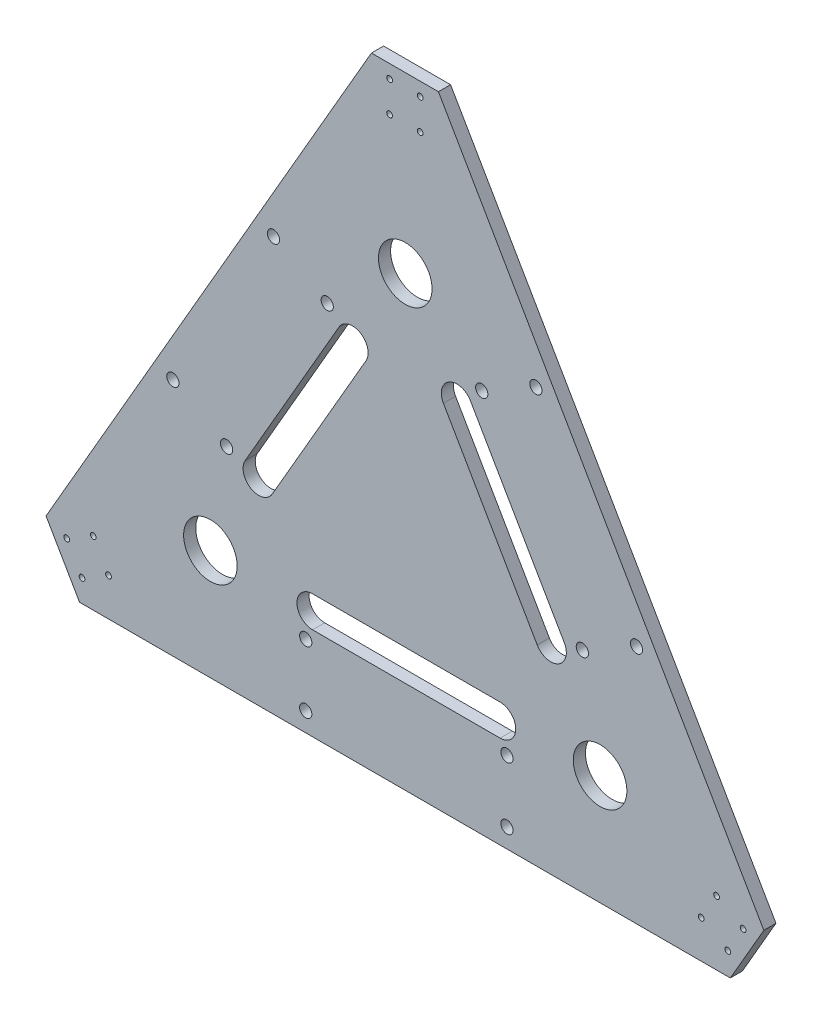
SolidWorks part; units mm, degrees
ref_plane "Front Plane" through (0, 0, 0) normal (0, 0, 1) x (1, 0, 0)
ref_plane "Top Plane" through (0, 0, 0) normal (0, 1, 0) x (1, 0, 0)
ref_plane "Right Plane" through (0, 0, 0) normal (1, 0, 0) x (0, 0, -1)
sketch "Sketch1" plane through (0, 0, 0) normal (0, 0, 1) x (1, 0, 0)
  line L0 (-647.4603, -317.6195) -> (-477.476, -23.1982)
  line L1 (-477.476, -23.1982) -> (-442.476, -23.1982)
  line L2 (-442.476, -23.1982) -> (-272.4917, -317.6195)
  line L3 (-272.4917, -317.6195) -> (-289.9917, -347.9304)
  line L4 (-289.9917, -347.9304) -> (-629.9603, -347.9304)
  line L5 (-629.9603, -347.9304) -> (-647.4603, -317.6195)
  line L6 (-432.8097, -158.7631) -> (-383.8097, -243.6336) construction
  line L7 (-425.7508, -154.6876) -> (-376.7508, -239.5581)
  line L8 (-439.8686, -162.8385) -> (-390.8686, -247.709)
  line L9 (-410.2405, -291.3785) -> (-508.2405, -291.3785) construction
  line L10 (-410.2405, -299.5293) -> (-508.2405, -299.5293)
  line L11 (-410.2405, -283.2276) -> (-508.2405, -283.2276)
  line L12 (-536.3734, -244.6163) -> (-487.3734, -159.7458) construction
  line L13 (-543.4323, -240.5408) -> (-494.4323, -155.6703)
  line L14 (-529.3145, -248.6917) -> (-480.3145, -163.8212)
  line L15 (-459.8079, -231.5859) -> (-432.8097, -158.7631) construction
  line L16 (-459.8079, -231.5859) -> (-459.8079, -114.0541) construction
  circle A1 centre (-581.2092, -222.8693) radius 3.2
  circle A2 centre (-528.6492, -131.8327) radius 3.2
  circle A3 centre (-500.5777, -148.0115) radius 3.2
  circle A4 centre (-553.1368, -239.0465) radius 3.2
  circle A13 centre (-367.2942, -238.2091) radius 3.2
  circle A14 centre (-419.8542, -147.1725) radius 3.2
  circle A15 centre (-391.5457, -131.4121) radius 3.2
  circle A16 centre (-338.9857, -222.4487) radius 3.2
  circle A17 centre (-511.8008, -305.5304) radius 3.2
  circle A18 centre (-406.6805, -305.5304) radius 3.2
  circle A19 centre (-406.6806, -337.9304) radius 3.2
  circle A20 centre (-511.8006, -337.9304) radius 3.2
  arc A21 (-425.7508, -154.6876) -> (-439.8686, -162.8385) centre (-432.8097, -158.7631) ccw
  arc A22 (-390.8686, -247.709) -> (-376.7508, -239.5581) centre (-383.8097, -243.6336) ccw
  arc A23 (-410.2405, -299.5293) -> (-410.2405, -283.2276) centre (-410.2405, -291.3785) ccw
  arc A24 (-508.2405, -283.2276) -> (-508.2405, -299.5293) centre (-508.2405, -291.3785) ccw
  arc A25 (-543.4323, -240.5408) -> (-529.3145, -248.6917) centre (-536.3734, -244.6163) ccw
  arc A26 (-480.3145, -163.8212) -> (-494.4323, -155.6703) centre (-487.3734, -159.7458) ccw
  circle A27 centre (-459.8079, -114.0541) radius 14
  circle A28 centre (-358.0223, -290.3519) radius 14
  circle A29 centre (-561.5935, -290.3519) radius 14
  point P6 (-526.8577, -193.5298)
  point P17 (-393.5776, -192.6927)
  point P18 (-408.3097, -201.1983)
  point P20 (-459.8079, -231.5859)
  point P29 (-459.2405, -305.5304)
  point P46 (-459.2405, -291.3785)
  point P53 (-511.8734, -202.181)
  dimension "D5" = 32.4
  dimension "D6" = 52.56
  dimension "D16" = 10
  dimension "D28" = 6.4
  dimension "D30" = 6.4
  dimension "D4" = 105.1182
  dimension "D7" = 105.12
  dimension "D8" = 32.4
  dimension "D9" = 10
  dimension "D10" = 42.4
  dimension "D11" = 52.56
  dimension "D12" = 110
  dimension "D13" = 10
  dimension "D14" = 105.12
  dimension "D15" = 110
  dimension "D17" = 32.4
  dimension "D18" = 77.6664
  dimension "D19" = 105.12
  dimension "D20" = 10
  dimension "D21" = 42.4
  dimension "D22" = 10
  dimension "D23" = 10
  dimension "D24" = 339.9685
  dimension "D25" = 32.4
  dimension "D27" = 52.56
  dimension "D29" = 105.12
  dimension "D31" = 42.4
  dimension "D33" = 3
  dimension "D36" = 3
sketch "Sketch2" plane through (0, 0, 0) normal (0, 0, 1) x (1, 0, 0)
  line L0 (-289.9917, -347.9304) -> (-629.9603, -347.9304) construction
  line L1 (-631.9603, -344.4663) -> (-645.4603, -321.0836)
  line L2 (-631.9603, -344.4663) -> (-605.9795, -329.4663)
  line L3 (-605.9795, -329.4663) -> (-619.4795, -306.0836)
  line L4 (-645.4603, -321.0836) -> (-619.4795, -306.0836)
  line L5 (-473.476, -23.1982) -> (-446.476, -23.1982)
  line L10 (-473.476, -23.1982) -> (-473.476, -53.1982)
  line L11 (-473.476, -53.1982) -> (-446.476, -53.1982)
  line L12 (-446.476, -23.1982) -> (-446.476, -53.1982)
  line L14 (-477.476, -23.1982) -> (-442.476, -23.1982) construction
  line L15 (-629.9603, -347.9304) -> (-647.4603, -317.6195) construction
  line L16 (-274.4867, -321.0749) -> (-287.9968, -344.4751)
  line L17 (-274.4867, -321.0749) -> (-300.4775, -306.0924)
  line L18 (-300.4775, -306.0924) -> (-313.9775, -329.475)
  line L19 (-287.9968, -344.4751) -> (-313.9775, -329.475)
  circle A0 centre (-636.6481, -322.3468) radius 1.5
  circle A1 centre (-628.6481, -336.2032) radius 1.5
  circle A2 centre (-614.7917, -328.2032) radius 1.5
  circle A3 centre (-622.7917, -314.3468) radius 1.5
  circle A8 centre (-451.976, -30.1982) radius 1.5
  circle A9 centre (-467.976, -30.1982) radius 1.5
  circle A10 centre (-467.976, -46.1982) radius 1.5
  circle A11 centre (-451.976, -46.1982) radius 1.5
  circle A12 centre (-291.3089, -336.2119) radius 1.5
  circle A13 centre (-283.309, -322.3555) radius 1.5
  circle A14 centre (-297.163, -314.3514) radius 1.5
  circle A15 centre (-305.1654, -328.2119) radius 1.5
  point P10 (-465.8216, -193.3804)
  point P41 (-459.976, -23.1982)
  point P44 (-459.976, -23.1982)
  point P50 (-638.7103, -332.775)
  point P51 (-638.7103, -332.775)
  dimension "D3" = 3
  dimension "D12" = 3
  dimension "D22" = 3
  dimension "D1" = 27
  dimension "D2" = 30
  dimension "D4" = 7
  dimension "D7" = 16
  dimension "D8" = 5.5
  dimension "D9" = 154.55
  dimension "D10" = 27
  dimension "D11" = 30
  dimension "D13" = 7
  dimension "D14" = 16
  dimension "D15" = 5.5
  dimension "D16" = 5.5
  dimension "D17" = 16
  dimension "D18" = 5.5
  dimension "D19" = 7
  dimension "D20" = 7
  dimension "D21" = 27
  dimension "D23" = 7
  dimension "D24" = 16
  dimension "D25" = 7
  dimension "D26" = 5.5
  dimension "D27" = 7
  dimension "D28" = 7
  dimension "D29" = 5.5
  dimension "D30" = 16
  dimension "D31" = 16
  dimension "D32" = 5.5
  dimension "D33" = 16
  dimension "D34" = 5.5
  dimension "D35" = 7
  dimension "D36" = 7
  dimension "D37" = 7
  dimension "D38" = 7
  dimension "D5" = 2
  dimension "D6" = 2
extrude "Boss-Extrude1" add sketch "Sketch1" along normal blind 6.35
extrude "Cut-Extrude1" cut sketch "Sketch2" along normal through all contours A11 | A12 | A9 | A8 | A10 | A13 | A14 | A15 | A2 | A3 | A1 | A0
sketch "Sketch3" plane through (0, 0, 0) normal (0, 0, 1) x (1, 0, 0)
  line L0 (-727.8827, -354.4911) -> (-485.048, 66.1109)
  line L1 (-485.048, 66.1109) -> (-435.048, 66.1109)
  line L2 (-435.048, 66.1109) -> (-192.2134, -354.4911)
  line L3 (-192.2134, -354.4911) -> (-217.2134, -397.7924)
  line L4 (-217.2134, -397.7924) -> (-702.8827, -397.7924)
  line L5 (-702.8827, -397.7924) -> (-727.8827, -354.4911)
  line L6 (-421.2391, -127.5533) -> (-351.2391, -248.7969) construction
  line L7 (-411.155, -121.7312) -> (-341.155, -242.9748)
  line L8 (-431.3232, -133.3754) -> (-361.3232, -254.6189)
  line L9 (-388.9974, -317.0038) -> (-528.9974, -317.0038) construction
  line L10 (-388.9974, -328.6479) -> (-528.9974, -328.6479)
  line L11 (-388.9974, -305.3597) -> (-528.9974, -305.3597)
  line L12 (-569.1872, -250.2007) -> (-499.1872, -128.9572) construction
  line L13 (-579.2713, -244.3787) -> (-509.2713, -123.1351)
  line L14 (-559.1031, -256.0228) -> (-489.1031, -134.7792)
  line L15 (-459.8079, -231.5859) -> (-421.2391, -127.5533) construction
  line L16 (-459.8079, -231.5859) -> (-459.8079, -63.6833) construction
  circle A1 centre (-624.0842, -194.7068) radius 3.2
  circle A2 centre (-571.5242, -103.6702) radius 3.2
  circle A3 centre (-543.4528, -119.849) radius 3.2
  circle A4 centre (-596.0118, -210.884) radius 3.2
  circle A13 centre (-324.3195, -210.4688) radius 3.2
  circle A14 centre (-376.8795, -119.4322) radius 3.2
  circle A15 centre (-348.571, -103.6718) radius 3.2
  circle A16 centre (-296.011, -194.7084) radius 3.2
  circle A17 centre (-512.3681, -355.3924) radius 3.2
  circle A18 centre (-407.2479, -355.3924) radius 3.2
  circle A19 centre (-407.248, -387.7924) radius 3.2
  circle A20 centre (-512.368, -387.7924) radius 3.2
  arc A21 (-411.155, -121.7312) -> (-431.3232, -133.3754) centre (-421.2391, -127.5533) ccw
  arc A22 (-361.3232, -254.6189) -> (-341.155, -242.9748) centre (-351.2391, -248.7969) ccw
  arc A23 (-388.9974, -328.6479) -> (-388.9974, -305.3597) centre (-388.9974, -317.0038) ccw
  arc A24 (-528.9974, -305.3597) -> (-528.9974, -328.6479) centre (-528.9974, -317.0038) ccw
  arc A25 (-579.2713, -244.3787) -> (-559.1031, -256.0228) centre (-569.1872, -250.2007) ccw
  arc A26 (-489.1031, -134.7792) -> (-509.2713, -123.1351) centre (-499.1872, -128.9572) ccw
  circle A27 centre (-459.8079, -63.6833) radius 20
  circle A28 centre (-314.3999, -315.5373) radius 20
  circle A29 centre (-605.2158, -315.5373) radius 20
  point P6 (-569.7327, -165.3673)
  point P17 (-350.6029, -164.9525)
  point P18 (-386.2391, -188.1751)
  point P20 (-459.8079, -231.5859)
  point P29 (-459.8079, -355.3924)
  point P46 (-458.9974, -317.0038)
  point P53 (-534.1872, -189.5789)
  dimension "D5" = 32.4
  dimension "D6" = 52.56
  dimension "D16" = 10
  dimension "D28" = 6.4
  dimension "D30" = 6.4
  dimension "D32" = 11.6441
  dimension "D35" = 40
  dimension "D4" = 105.1182
  dimension "D7" = 105.12
  dimension "D8" = 32.4
  dimension "D9" = 10
  dimension "D10" = 42.4
  dimension "D11" = 52.56
  dimension "D12" = 110
  dimension "D13" = 10
  dimension "D14" = 140
  dimension "D15" = 110
  dimension "D17" = 32.4
  dimension "D18" = 32.4
  dimension "D19" = 105.12
  dimension "D20" = 10
  dimension "D21" = 42.4
  dimension "D22" = 10
  dimension "D23" = 10
  dimension "D24" = 32.4
  dimension "D25" = 32.4
  dimension "D26" = 105.12
  dimension "D27" = 52.56
  dimension "D29" = 105.12
  dimension "D31" = 42.4
  dimension "D34" = 110.952
  dimension "D37" = 167.9027
  dimension "D33" = 3
  dimension "D36" = 3
